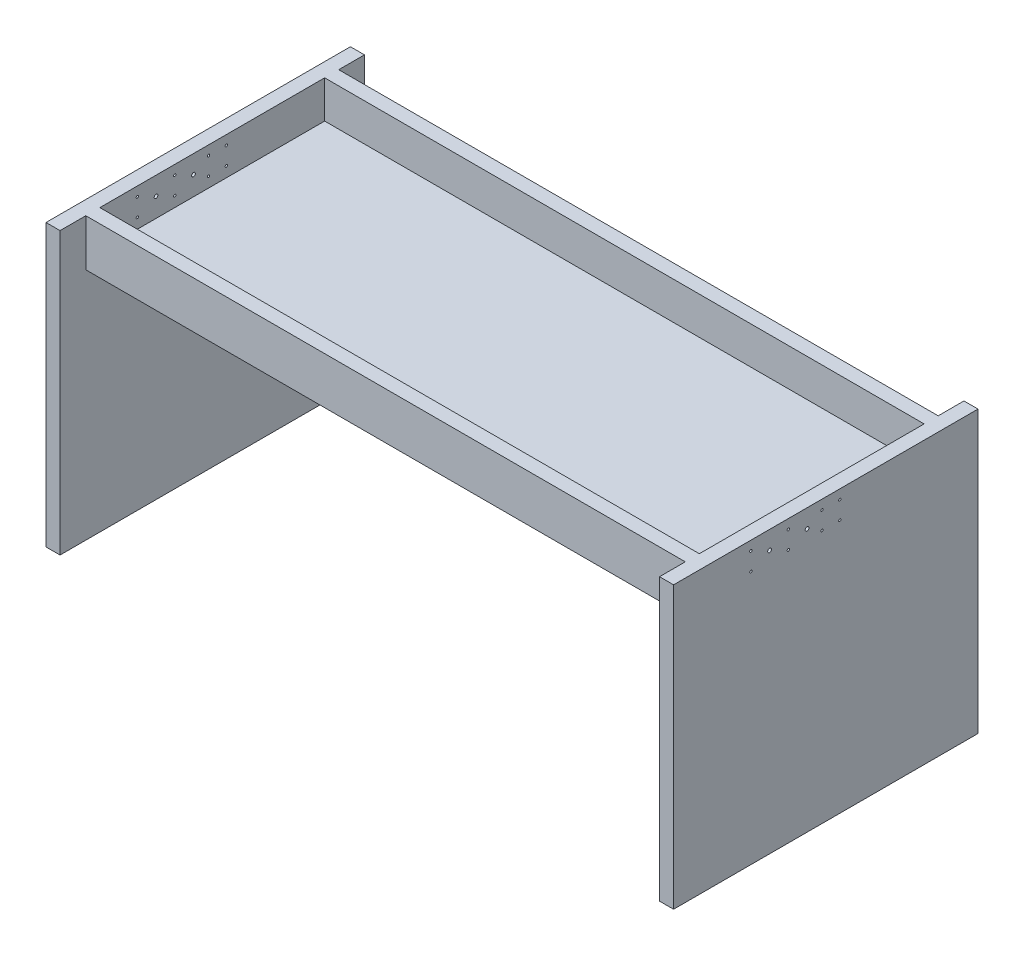
SolidWorks part; units mm, degrees
ref_plane "Front Plane" through (0, 0, 0) normal (0, 0, 1) x (1, 0, 0)
ref_plane "Top Plane" through (0, 0, 0) normal (0, 1, 0) x (1, 0, 0)
ref_plane "Right Plane" through (0, 0, 0) normal (1, 0, 0) x (0, 0, -1)
sketch "Sketch1" plane through (0, 0, 0) normal (0, 1, 0) x (1, 0, 0)
  line L1 (-670, -270) -> (670, -270)
  line L2 (-670, -270) -> (-670, 270)
  line L3 (-670, 270) -> (670, 270)
  line L4 (670, -270) -> (670, 270)
  line L5 (-670, -270) -> (670, 270) construction
  line L6 (-670, 270) -> (670, -270) construction
  point P0 (0, 0)
  dimension "D1" = 540
  dimension "D2" = 1340
extrude "Boss-Extrude1" add sketch "Sketch1" along normal blind 100
sketch "Sketch2" plane through (0, 100, 0) normal (0, 1, 0) x (1, 0, 0)
  line L0 (670, 270) -> (-670, 270) construction
  line L1 (-640, -240) -> (640, -240)
  line L2 (-640, -240) -> (-640, 240)
  line L3 (-640, 240) -> (640, 240)
  line L4 (640, -240) -> (640, 240)
  line L5 (-640, -240) -> (640, 240) construction
  line L6 (-640, 240) -> (640, -240) construction
  line L7 (-670, 270) -> (-670, -270) construction
  point P0 (0, 0)
  dimension "D1" = 30
  dimension "D2" = 30
  dimension "D3" = 480
extrude "Cut-Extrude1" cut sketch "Sketch2" against normal blind 80
ref_plane "Plane2" through (-640, 0, 0) normal (1, 0, 0) x (0, 0, -1)
sketch "Sketch6" plane through (-640, 0, 0) normal (1, 0, 0) x (0, 0, -1)
  line L0 (-270, 100) -> (270, 100) construction
  line L1 (-325, -500) -> (325, -500)
  line L2 (-325, -500) -> (-325, 100)
  line L3 (-325, 100) -> (325, 100)
  line L4 (325, -500) -> (325, 100)
  line L5 (-325, -500) -> (325, 100) construction
  line L6 (-325, 100) -> (325, -500) construction
  point P0 (0, -200)
  point P5 (0, 0)
  dimension "D1" = 600
  dimension "D2" = 650
  dimension "D3" = 0
extrude "Boss-Extrude3" add sketch "Sketch6" against normal blind 30
mirror "Mirror3" about plane through (0, 0, 0) normal (1, 0, 0) of "Boss-Extrude3"
sketch "Sketch10" plane through (-640, 0, 0) normal (1, 0, 0) x (0, 0, -1)
  line L0 (240, 100) -> (-240, 100) construction
  line L2 (-240, 20) -> (-240, 100) construction
  circle A0 centre (-160, 80) radius 2.5
  circle A1 centre (-160, 42) radius 2.5
  circle A2 centre (-80, 42) radius 2.5
  circle A3 centre (-80, 80) radius 2.5
  circle A4 centre (30, 80) radius 2.5
  circle A5 centre (30, 42) radius 2.5
  circle A6 centre (-8, 42) radius 2.5
  circle A7 centre (-8, 80) radius 2.5
  point P16 (0, 0)
  dimension "D1" = 5
  dimension "D2" = 80
  dimension "D3" = 38
  dimension "D4" = 72
  dimension "D5" = 20
  dimension "D7" = 80
  dimension "D6" = 38
extrude "Cut-Extrude3" cut sketch "Sketch10" against normal blind 80
mirror "Mirror4" about plane through (0, 0, 0) normal (1, 0, 0) of "Cut-Extrude3"
sketch "Sketch11" plane through (-640, 0, 0) normal (1, 0, 0) x (0, 0, -1)
  line L0 (240, 100) -> (-240, 100) construction
  circle A0 centre (-40, 61) radius 4
  circle A1 centre (-120, 61) radius 4
  circle A3 centre (-80, 80) radius 2.5 construction
  dimension "D1" = 8
  dimension "D2" = 8
  dimension "D3" = 40
  dimension "D4" = 40
  dimension "D5" = 39
extrude "Cut-Extrude4" cut sketch "Sketch11" against normal blind 80
mirror "Mirror5" about plane through (0, 0, 0) normal (1, 0, 0) of "Cut-Extrude4"
